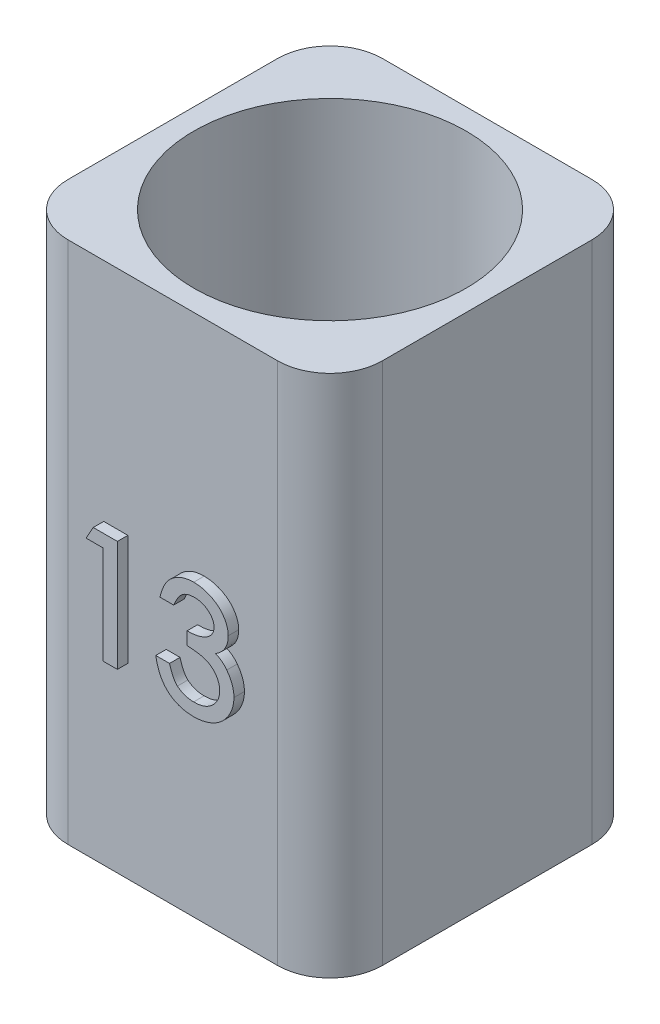
SolidWorks part; units mm, degrees
ref_plane "Ebene vorne" through (0, 0, 0) normal (0, 0, 1) x (1, 0, 0)
ref_plane "Ebene oben" through (0, 0, 0) normal (0, 1, 0) x (1, 0, 0)
ref_plane "Ebene rechts" through (0, 0, 0) normal (1, 0, 0) x (0, 0, -1)
sketch "Sketch1" plane through (0, 0, 0) normal (0, 1, 0) x (1, 0, 0)
  line L1 (7.5, -7.5) -> (-7.5, -7.5)
  line L2 (7.5, -7.5) -> (7.5, 7.5)
  line L3 (7.5, 7.5) -> (-7.5, 7.5)
  line L4 (-7.5, -7.5) -> (-7.5, 7.5)
  line L5 (7.5, -7.5) -> (-7.5, 7.5) construction
  line L6 (7.5, 7.5) -> (-7.5, -7.5) construction
  point P0 (0, 0)
  dimension "D1" = 15
  dimension "D2" = 15
extrude "Boss-Extrude1" add sketch "Sketch1" along normal blind 25
sketch "Sketch2" plane through (0, 25, 0) normal (0, 1, 0) x (1, 0, 0)
  circle A0 centre (0, 0) radius 6.5
  dimension "D1" = 13
extrude "Cut-Extrude1" cut sketch "Sketch2" against normal offset from surface (24 mm away) 1 up to face at (0, 0, 0)
sketch "Sketch3" plane through (0, 0, 7.5) normal (0, 0, 1) x (1, 0, 0)
  text T0 "<b>13</b>" font "Century Gothic" height in points 20
extrude "Boss-Extrude3" add sketch "Sketch3" along normal blind 0.5
fillet "Fillet1" radius 2.5 1 edges at (-7.5, 12.5, 7.5)
fillet "Fillet2" radius 2.5 1 edges at (7.5, 12.5, 7.5)
fillet "Fillet3" radius 2.5 1 edges at (7.5, 12.5, -7.5)
fillet "Fillet4" radius 2.5 1 edges at (-7.5, 12.5, -7.5)
